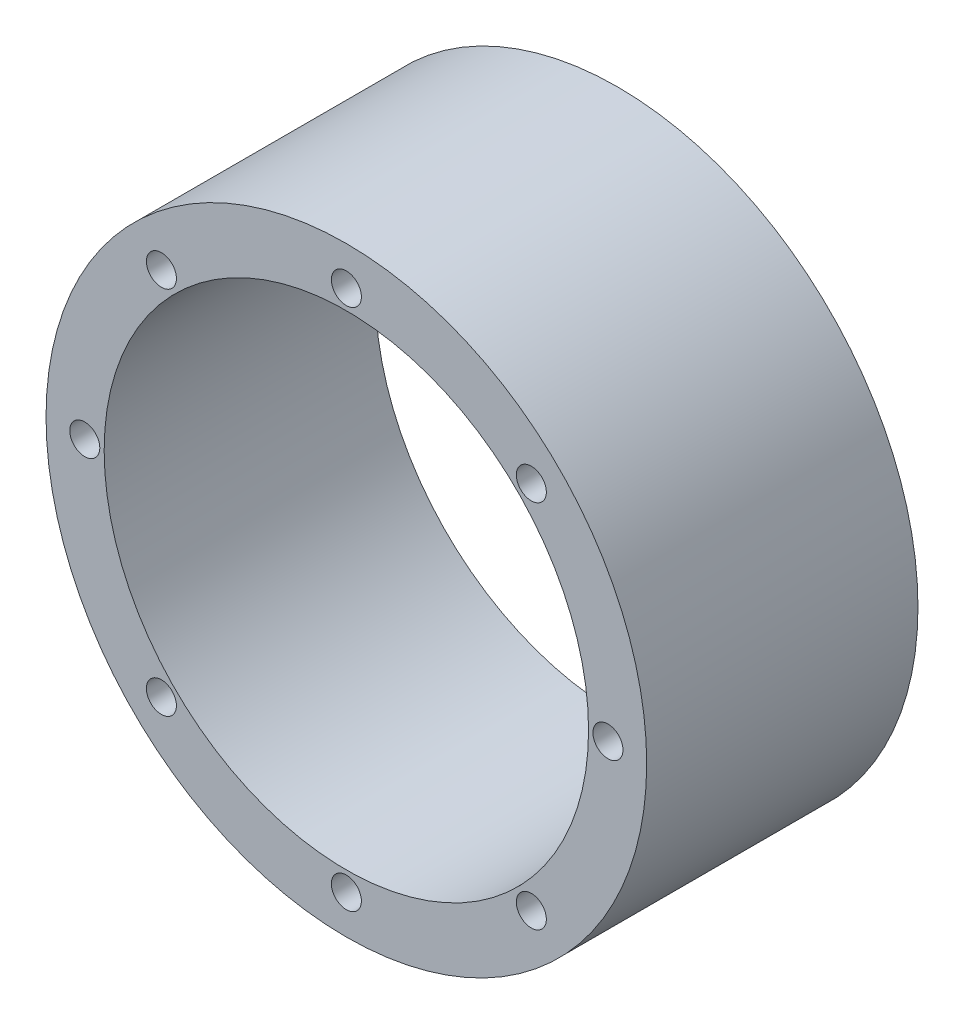
SolidWorks part; units mm, degrees
ref_plane "Front Plane" through (0, 0, 0) normal (0, 0, 1) x (1, 0, 0)
ref_plane "Top Plane" through (0, 0, 0) normal (0, 1, 0) x (1, 0, 0)
ref_plane "Right Plane" through (0, 0, 0) normal (1, 0, 0) x (0, 0, -1)
sketch "Sketch1" plane through (0, 0, 0) normal (0, 0, 1) x (1, 0, 0)
  circle A0 centre (0, 0) radius 27 construction
  circle A1 centre (-27, 0) radius 1.55
  circle A2 centre (-19.0919, 19.0919) radius 1.55
  circle A3 centre (0, 27) radius 1.55
  circle A4 centre (19.0919, 19.0919) radius 1.55
  circle A5 centre (27, 0) radius 1.55
  circle A6 centre (19.0919, -19.0919) radius 1.55
  circle A7 centre (0, -27) radius 1.55
  circle A8 centre (-19.0919, -19.0919) radius 1.55
  circle A9 centre (0, 0) radius 24 construction
  circle A10 centre (0, 0) radius 25
  circle A11 centre (0, 0) radius 31
  point P21 (0, 0)
  dimension "D1" = 8
extrude "Boss-Extrude1" add sketch "Sketch1" along normal blind 28
